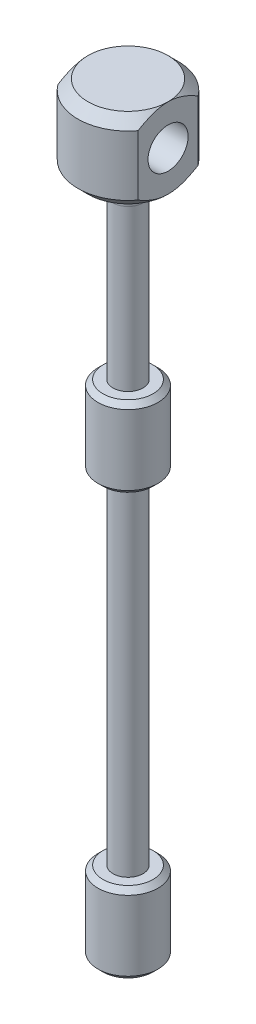
SolidWorks part; units mm, degrees
material "AISI 1035 Steel (SS)"
ref_plane "Front Plane" through (0, 0, 0) normal (0, 0, 1) x (1, 0, 0)
ref_plane "Top Plane" through (0, 0, 0) normal (0, 1, 0) x (1, 0, 0)
ref_plane "Right Plane" through (0, 0, 0) normal (1, 0, 0) x (0, 0, -1)
sketch "Sketch1" plane through (0, 0, 0) normal (0, 1, 0) x (1, 0, 0)
  circle A0 centre (0, 0) radius 1.5
  dimension "D1" = 3
extrude "Boss-Extrude1" add sketch "Sketch1" along normal mid plane 34
sketch "Sketch3" plane through (0, -17, 0) normal (0, -1, 0) x (1, 0, 0)
  circle A0 centre (0, 0) radius 3
  dimension "D1" = 6
extrude "Boss-Extrude2" add sketch "Sketch3" along normal blind 8
mirror "Mirror1" about plane through (0, 0, 0) normal (0, 1, 0) of "Boss-Extrude2"
sketch "Sketch4" plane through (0, 25, 0) normal (0, 1, 0) x (1, 0, 0)
  circle A0 centre (0, 0) radius 1.5
  dimension "D1" = 3
extrude "Boss-Extrude3" add sketch "Sketch4" along normal blind 18
sketch "Sketch5" plane through (0, 43, 0) normal (0, 1, 0) x (1, 0, 0)
  circle A0 centre (0, 0) radius 5
  dimension "D1" = 10
extrude "Boss-Extrude4" add sketch "Sketch5" along normal blind 8 contours A0
chamfer "Chamfer1" distance 1 angle 45 2 edges at (0, 43, 5) (0, 51, 5)
chamfer "Chamfer2" distance 0.5 angle 45 4 edges at (0, -25, -3) (0, -17, -3) (0, 17, -3) (0, 25, -3)
sketch "Sketch6" plane through (0, 51, 0) normal (0, 1, 0) x (1, 0, 0)
  line L0 (-4, 3) -> (-4, -3)
  line L1 (4, 3) -> (4, -3)
  arc A0 (-4, 3) -> (-4, -3) centre (0, 0) ccw
  arc A1 (4, -3) -> (4, 3) centre (0, 0) ccw
  dimension "D3" = 10
  dimension "D1" = 4
  dimension "D2" = 4
extrude "Cut-Extrude1" cut sketch "Sketch6" against normal blind 12
sketch "Sketch7" plane through (-4, 0, 0) normal (-1, 0, 0) x (0, 0, 1)
  line L0 (4, 51) -> (0, 51) construction
  circle A0 centre (0, 47) radius 2
  dimension "D1" = 4
  dimension "D2" = 4
extrude "Cut-Extrude2" cut sketch "Sketch7" against normal blind 12
fillet "Fillet1" radius 2 1 edges at (0, 43, 1.5)
